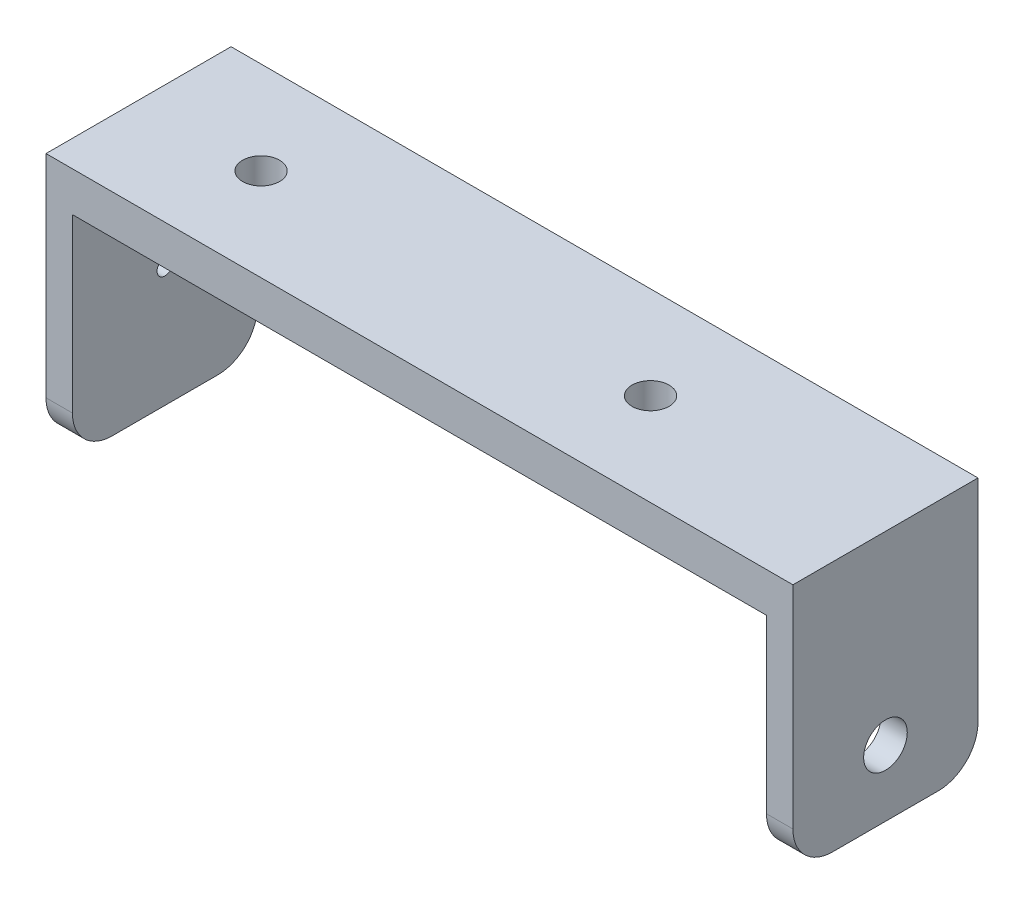
SolidWorks part; units mm, degrees
ref_plane "前视基准面" through (0, 0, 0) normal (0, 0, 1) x (1, 0, 0)
ref_plane "上视基准面" through (0, 0, 0) normal (0, 1, 0) x (1, 0, 0)
ref_plane "右视基准面" through (0, 0, 0) normal (1, 0, 0) x (0, 0, -1)
sketch "草图1" plane through (0, 0, 0) normal (0, 0, 1) x (1, 0, 0)
  line L0 (-28.25, 0) -> (-28.25, 19)
  line L1 (-28.25, 19) -> (28.25, 19)
  line L2 (28.25, 19) -> (28.25, 0)
  line L3 (28.25, 0) -> (26.25, 0)
  line L4 (26.25, 0) -> (26.25, 16)
  line L5 (26.25, 16) -> (-26.25, 16)
  line L6 (-26.25, 16) -> (-26.25, 0)
  line L7 (-26.25, 0) -> (-28.25, 0)
  line L8 (-61.4321, 26.241) -> (-59.0057, 26.241)
  line L9 (0, 0) -> (0, 21.894) construction
  dimension "D1" = 56.5
  dimension "D2" = 19
  dimension "D3" = 3
  dimension "D4" = 2
  dimension "D5" = 2
  dimension "D6" = 19
extrude "凸台-拉伸1" add sketch "草图1" along normal blind 14 contours L5 L9 L1 L0 L7 L6 | L9 L5 L4 L3 L2 L1
sketch "草图2" plane through (28.25, 0, 0) normal (1, 0, 0) x (0, 0, -1)
  line L0 (-7, 0) -> (-7, 19) construction
  line L1 (-14, 0) -> (0, 0) construction
  line L2 (-14, 19) -> (0, 19) construction
  circle A0 centre (-7, 5) radius 1.65
  dimension "D2" = 3.3
  dimension "D1" = 5
extrude "切除-拉伸1" cut sketch "草图2" against normal up to surface (2 mm away) up to face at (26.25, 8, 7)
sketch "草图3" plane through (0, 19, 0) normal (0, 1, 0) x (1, 0, 0)
  line L0 (-28.25, -7) -> (28.25, -7) construction
  line L1 (-28.25, -14) -> (-28.25, 0) construction
  line L2 (28.25, -14) -> (28.25, 0) construction
  line L3 (0, 0) -> (0, -14) construction
  line L4 (-28.25, 0) -> (28.25, 0) construction
  line L5 (-28.25, -14) -> (28.25, -14) construction
  line L6 (-4.25, 0) -> (-4.25, -14) construction
  circle A0 centre (-18.98, -7) radius 1.4
  circle A1 centre (10.48, -7) radius 1.4
  dimension "D2" = 2.8
  dimension "D1" = 29.46
  dimension "D3" = 4.25
extrude "切除-拉伸2" cut sketch "草图3" against normal blind 14
fillet "圆角1" radius 3 4 edges at (27.25, 0, 0) (27.25, 0, 14) (-27.25, 0, 0) (-27.25, 0, 14)
sketch "草图5" plane through (-28.25, 0, 0) normal (-1, 0, 0) x (0, 0, 1)
  line L0 (7, 5) -> (7, 20.3188) construction
  circle A0 centre (7, 5) radius 1.65 construction
  circle A1 centre (7, 5) radius 1.65 construction
  circle A2 centre (7, 9.085) radius 0.6
  circle A3 centre (7, 13.085) radius 0.6
  dimension "D1" = 1.2
  dimension "D2" = 4.085
  dimension "D3" = 8.085
extrude "切除-拉伸3" cut sketch "草图5" against normal blind 10
